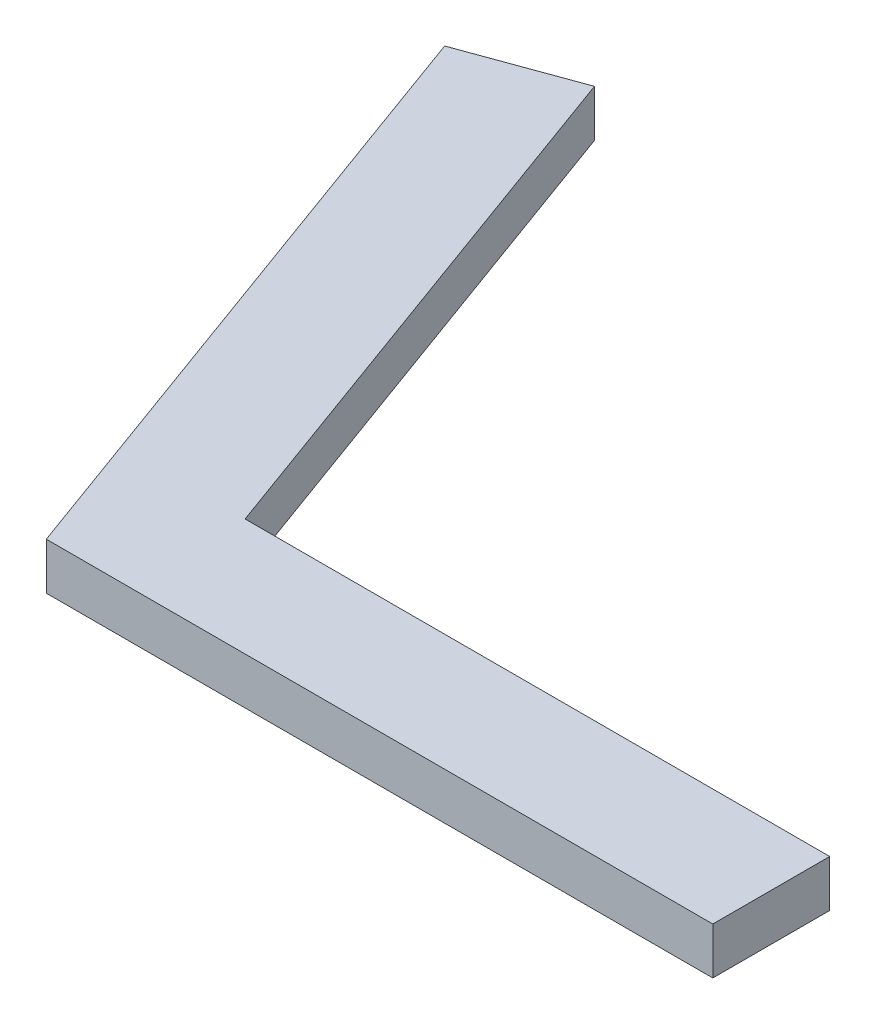
SolidWorks part; units mm, degrees
ref_plane "Front Plane" through (0, 0, 0) normal (0, 0, 1) x (1, 0, 0)
ref_plane "Top Plane" through (0, 0, 0) normal (0, 1, 0) x (1, 0, 0)
ref_plane "Right Plane" through (0, 0, 0) normal (1, 0, 0) x (0, 0, -1)
sketch "Sketch1" plane through (0, 0, 0) normal (0, 1, 0) x (1, 0, 0)
  line L0 (31.75, 0) -> (0, 0)
  line L1 (0, 0) -> (-10.8591, 29.8352)
  line L2 (-10.8591, 29.8352) -> (-16.8262, 27.6634)
  line L3 (-16.8262, 27.6634) -> (-4.4463, -6.35)
  line L4 (-4.4463, -6.35) -> (31.75, -6.35)
  line L5 (31.75, -6.35) -> (31.75, 0)
  dimension "D1" = 110
  dimension "D2" = 6.35
  dimension "D3" = 31.75
extrude "Boss-Extrude1" add sketch "Sketch1" along normal blind 2.54
